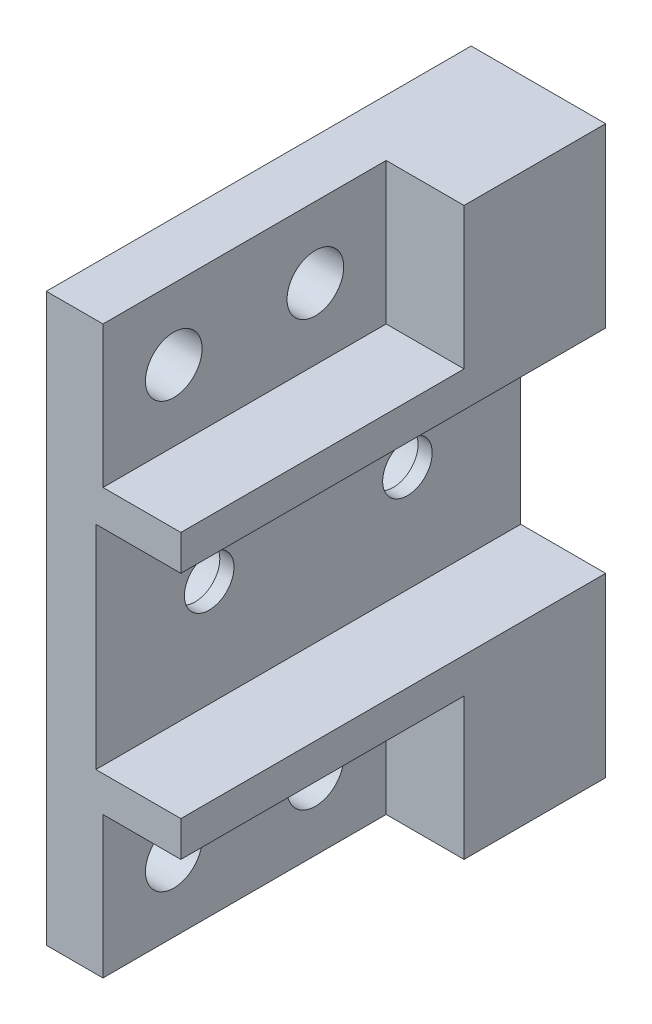
SolidWorks part; units mm, degrees
ref_plane "Plan de face" through (0, 0, 0) normal (0, 0, 1) x (1, 0, 0)
ref_plane "Plan de dessus" through (0, 0, 0) normal (0, 1, 0) x (1, 0, 0)
ref_plane "Plan de droite" through (0, 0, 0) normal (1, 0, 0) x (0, 0, -1)
sketch "Esquisse1" plane through (0, 0, 0) normal (0, 0, 1) x (1, 0, 0)
  line L0 (9.5, 20) -> (9.5, 17.5)
  line L1 (0, 0) -> (9.5, 0)
  line L2 (0, 0) -> (0, 20)
  line L3 (0, 20) -> (9.5, 20)
  line L4 (9.5, 17.5) -> (3.5, 17.5)
  line L5 (3.5, 17.5) -> (3.5, 2.5)
  line L6 (3.5, 2.5) -> (9.5, 2.5)
  line L7 (9.5, 2.5) -> (9.5, 0)
  dimension "D2" = 20
  dimension "D3" = 15
  dimension "D4" = 6
  dimension "D5" = 3.5
extrude "Boss.-Extru.1" add sketch "Esquisse1" along normal blind 30
sketch "Esquisse2" plane through (3.5, 0, 0) normal (1, 0, 0) x (0, 0, -1)
  line L0 (30, 10) -> (-30, 10) construction
  line L2 (-30, 2.5) -> (-30, 17.5) construction
  line L3 (0, 2.5) -> (0, 17.5) construction
  circle A0 centre (-22, 10) radius 1.75
  circle A1 centre (-8, 10) radius 1.75
  point P7 (0, 10)
  dimension "D1" = 3.5
  dimension "D2" = 14
  dimension "D3" = 8
extrude "Enlèv. mat.-Extru.1" cut sketch "Esquisse2" against normal through all
sketch "Esquisse3" plane through (0, 0, 0) normal (-1, 0, 0) x (0, 0, 1)
  circle A0 centre (8, 10) radius 3
  circle A1 centre (22, 10) radius 3
  dimension "D1" = 6
  dimension "D2" = 6
extrude "Enlèv. mat.-Extru.2" cut sketch "Esquisse3" against normal blind 2.5
sketch "Esquisse4" plane through (0, 0, 0) normal (-1, 0, 0) x (0, 0, 1)
  line L0 (29.5, 25) -> (-0.5, 25) construction
  line L1 (30, 0) -> (0, 0)
  line L2 (30, 0) -> (30, -10)
  line L3 (30, -10) -> (0, -10)
  line L4 (0, 0) -> (0, -10)
  line L5 (0, 20) -> (30, 20)
  line L6 (0, 20) -> (0, 30)
  line L7 (0, 30) -> (30, 30)
  line L8 (30, 20) -> (30, 30)
  line L9 (29.5, -5) -> (-0.5, -5) construction
  circle A0 centre (15, -5) radius 2
  circle A1 centre (5, -5) radius 2
  circle A2 centre (15, 25) radius 2
  circle A3 centre (25, -5) radius 2
  circle A4 centre (5, 25) radius 2
  circle A5 centre (25, 25) radius 2
  dimension "D3" = 4
  dimension "D4" = 3
  dimension "D5" = 2
  dimension "D6" = 5
  dimension "D1" = 10
  dimension "D2" = 10
  dimension "D7" = 30
  dimension "D8" = 30
  dimension "D9" = 5
  dimension "D10" = 5
  dimension "D11" = 5
  dimension "D12" = 10
  dimension "D13" = 5
extrude "Boss.-Extru.2" add sketch "Esquisse4" against normal blind 4
sketch "Esquisse5" plane through (0, 0, 0) normal (0, 0, -1) x (-1, 0, 0)
  line L0 (-4, 0) -> (-9.5, 0) construction
  line L1 (-9.5, 17.5) -> (0, 17.5)
  line L2 (-9.5, 17.5) -> (-9.5, 30)
  line L3 (-9.5, 30) -> (0, 30)
  line L4 (0, 17.5) -> (0, 30)
  line L5 (-9.5, 0) -> (0, 0)
  line L6 (-9.5, 0) -> (-9.5, -10)
  line L7 (-9.5, -10) -> (0, -10)
  line L8 (0, 0) -> (0, -10)
extrude "Boss.-Extru.3" add sketch "Esquisse5" against normal blind 10
sketch "Esquisse6" plane through (0, 0, 0) normal (0, 0, -1) x (-1, 0, 0)
  line L0 (0, 10) -> (-14.3576, 10) construction
  line L1 (0, 30) -> (0, -10) construction
  circle A0 centre (-5, 25) radius 3
  circle A1 centre (-5, -5) radius 3
  dimension "D3" = 6
  dimension "D4" = 6
  dimension "D1" = 15
  dimension "D2" = 15
  dimension "D5" = 5
  dimension "D6" = 5
extrude "Enlèv. mat.-Extru.3" cut sketch "Esquisse6" against normal blind 8
sketch "Esquisse7" plane through (0, 0, 0) normal (-1, 0, 0) x (0, 0, 1)
  line L0 (30, 10) -> (0, 10) construction
  line L1 (30, 30) -> (30, -10) construction
  line L2 (0, 30) -> (0, -10) construction
